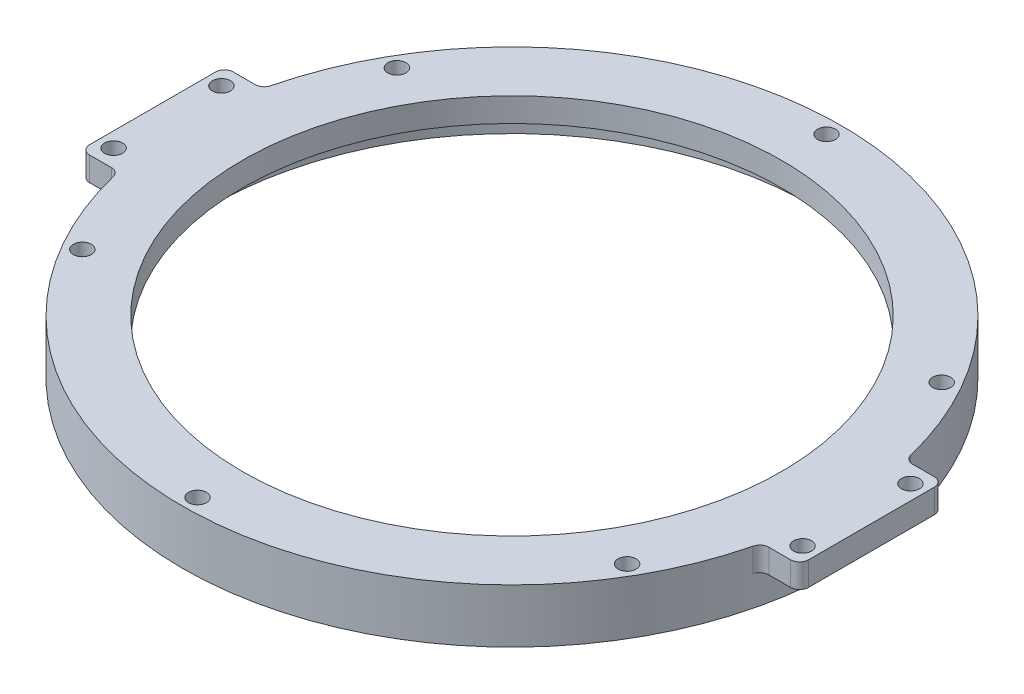
SolidWorks part; units mm, degrees
ref_plane "前视基准面" through (0, 0, 0) normal (0, 0, 1) x (1, 0, 0)
ref_plane "上视基准面" through (0, 0, 0) normal (0, 1, 0) x (1, 0, 0)
ref_plane "右视基准面" through (0, 0, 0) normal (1, 0, 0) x (0, 0, -1)
other "Configuration Table"
sketch "草图1" plane through (0, 0, 0) normal (0, 1, 0) x (1, 0, 0)
  line L0 (0, 0) -> (0, -50000) construction
  line L1 (0, 0) -> (-50000, 0) construction
  line L2 (-54.8635, 12) -> (-58.5, 12)
  line L3 (-60, 10.5) -> (-60, -10.5)
  line L4 (-58.5, -12) -> (-54.8635, -12)
  line L5 (58.5, -12) -> (54.8635, -12)
  line L6 (60, 10.5) -> (60, -10.5)
  line L7 (54.8635, 12) -> (58.5, 12)
  arc A0 (-53.4069, -13.1416) -> (53.4069, -13.1416) centre (0, 0) ccw
  circle A1 centre (0, 0) radius 45
  circle A2 centre (-57.5, 9) radius 1.5
  circle A3 centre (-57.5, -9) radius 1.5
  arc A4 (-60, -10.5) -> (-58.5, -12) centre (-58.5, -10.5) ccw
  arc A5 (-58.5, 12) -> (-60, 10.5) centre (-58.5, 10.5) ccw
  circle A6 centre (57.5, 9) radius 1.5
  circle A7 centre (57.5, -9) radius 1.5
  arc A8 (60, -10.5) -> (58.5, -12) centre (58.5, -10.5) cw
  arc A9 (58.5, 12) -> (60, 10.5) centre (58.5, 10.5) cw
  arc A10 (53.4069, 13.1416) -> (-53.4069, 13.1416) centre (0, 0) ccw
  arc A11 (54.8635, 12) -> (53.4069, 13.1416) centre (54.8635, 13.5) cw
  arc A12 (54.8635, -12) -> (53.4069, -13.1416) centre (54.8635, -13.5) ccw
  arc A13 (-54.8635, -12) -> (-53.4069, -13.1416) centre (-54.8635, -13.5) cw
  arc A14 (-54.8635, 12) -> (-53.4069, 13.1416) centre (-54.8635, 13.5) ccw
  circle A15 centre (0, 52.5) radius 1.5
  circle A16 centre (45.4663, 26.25) radius 1.5
  circle A17 centre (0, 0) radius 45
  circle A18 centre (45.4663, -26.25) radius 1.5
  circle A19 centre (0, 0) radius 45
  circle A20 centre (0, -52.5) radius 1.5
  circle A21 centre (0, 0) radius 45
  circle A22 centre (-45.4663, -26.25) radius 1.5
  circle A23 centre (0, 0) radius 45
  circle A24 centre (-45.4663, 26.25) radius 1.5
  circle A25 centre (0, 0) radius 45
  point P33 (53.6749, 12)
  point P36 (53.6749, -12)
  point P39 (-53.6749, -12)
  point P42 (-53.6749, 12)
  point P63 (0, 0)
  dimension "D1" = 110
  dimension "D2" = 90
  dimension "D5" = 3
  dimension "D6" = 3
  dimension "D9" = 1.5
  dimension "D10" = 1.5
  dimension "D11" = 3
  dimension "D3" = 24
  dimension "D4" = 60
  dimension "D7" = 9
  dimension "D8" = 57.5
  dimension "D12" = 52.5
  dimension "D13" = 6
extrude "凸台-拉伸1" add sketch "草图1" along normal blind 4 contours A14 L2 A5 L3 A4 L4 A13 A0 A12 L5 A8 L6 A9 L7 A11 A10 A24 A22 A20 A18 A16 A15 A6 A3 A2 A1 A7
sketch "草图2" plane through (0, 0, 0) normal (0, 1, 0) x (1, 0, 0)
  circle A0 centre (0, 0) radius 55
  circle A1 centre (0, 0) radius 50
  circle A2 centre (0, 52.5) radius 1.5
  circle A3 centre (45.4663, 26.25) radius 1.5
  circle A4 centre (0, 0) radius 55
  circle A5 centre (45.4663, -26.25) radius 1.5
  circle A6 centre (0, 0) radius 55
  circle A7 centre (0, -52.5) radius 1.5
  circle A8 centre (0, 0) radius 55
  circle A9 centre (-45.4663, -26.25) radius 1.5
  circle A10 centre (0, 0) radius 55
  circle A11 centre (-45.4663, 26.25) radius 1.5
  circle A12 centre (0, 0) radius 55
  point P25 (0, 0)
  dimension "D1" = 110
  dimension "D2" = 100
  dimension "D3" = 6
extrude "凸台-拉伸2" add sketch "草图2" against normal blind 5 contours A0 A11 A9 A7 A5 A3 A2 A1
